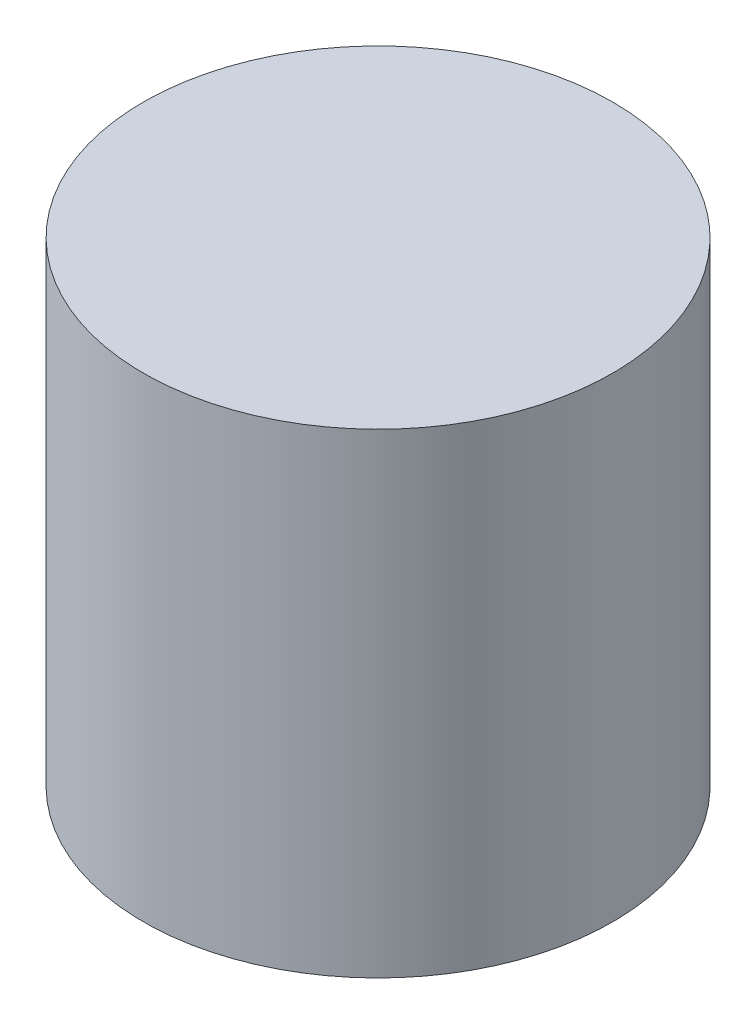
SolidWorks part; units mm, degrees
ref_plane "Front Plane" through (0, 0, 0) normal (0, 0, 1) x (1, 0, 0)
ref_plane "Top Plane" through (0, 0, 0) normal (0, 1, 0) x (1, 0, 0)
ref_plane "Right Plane" through (0, 0, 0) normal (1, 0, 0) x (0, 0, -1)
sketch "Sketch1" plane through (0, 0, 0) normal (0, 1, 0) x (1, 0, 0)
  circle A0 centre (0, 0) radius 3.1242
  dimension "D1" = 6.2484
extrude "Boss-Extrude1" add sketch "Sketch1" along normal blind 6.3246
